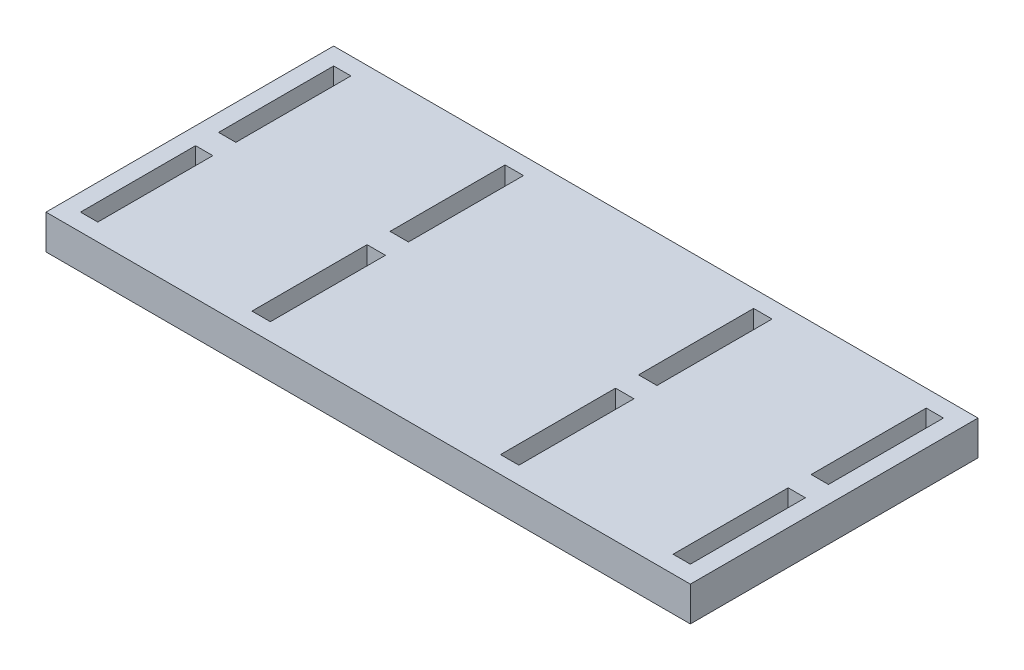
SolidWorks part; units mm, degrees
ref_plane "前视基准面" through (0, 0, 0) normal (0, 0, 1) x (1, 0, 0)
ref_plane "上视基准面" through (0, 0, 0) normal (0, 1, 0) x (1, 0, 0)
ref_plane "右视基准面" through (0, 0, 0) normal (1, 0, 0) x (0, 0, -1)
other "Configuration Table"
sketch "草图1" plane through (0, 0, 0) normal (0, 1, 0) x (1, 0, 0)
  line L0 (56, 0) -> (56, -50)
  line L1 (0, 0) -> (112, 0)
  line L2 (0, 0) -> (0, -50)
  line L3 (0, -50) -> (112, -50)
  line L4 (112, 0) -> (112, -50)
  line L5 (3, -3) -> (6, -3)
  line L6 (3, -3) -> (3, -23)
  line L7 (3, -23) -> (6, -23)
  line L8 (6, -3) -> (6, -23)
  line L9 (0, -25) -> (107.5621, -25)
  line L10 (3, -27) -> (6, -27)
  line L11 (6, -47) -> (6, -27)
  line L12 (3, -47) -> (6, -47)
  line L13 (3, -47) -> (3, -27)
  line L14 (109, -23) -> (106, -23)
  line L15 (106, -3) -> (106, -23)
  line L16 (109, -3) -> (106, -3)
  line L17 (109, -3) -> (109, -23)
  line L18 (109, -47) -> (109, -27)
  line L19 (109, -47) -> (106, -47)
  line L20 (106, -47) -> (106, -27)
  line L21 (109, -27) -> (106, -27)
  line L22 (32.8, -27) -> (36, -27)
  line L23 (32.8, -3) -> (36, -3)
  line L24 (32.8, -3) -> (32.8, -23)
  line L25 (32.8, -23) -> (36, -23)
  line L26 (36, -3) -> (36, -23)
  line L27 (36, -47) -> (36, -27)
  line L28 (32.8, -47) -> (36, -47)
  line L29 (32.8, -47) -> (32.8, -27)
  line L30 (79.2, -47) -> (79.2, -27)
  line L31 (79.2, -47) -> (76, -47)
  line L32 (76, -47) -> (76, -27)
  line L33 (79.2, -27) -> (76, -27)
  line L34 (79.2, -23) -> (76, -23)
  line L35 (76, -3) -> (76, -23)
  line L36 (79.2, -3) -> (76, -3)
  line L37 (79.2, -3) -> (79.2, -23)
  dimension "D1" = 112
  dimension "D2" = 50
  dimension "D3" = 3
  dimension "D4" = 3
  dimension "D5" = 20
  dimension "D6" = 3
  dimension "D7" = 3.2
  dimension "D8" = 20
  dimension "D9" = 20
extrude "凸台-拉伸1" add sketch "草图1" along normal blind 6 contours L2 L9 L0 L1 L5 L8 L7 L6 | L9 L2 L3 L0 L12 L13 L10 L11 | L0 L9 L4 L1 L16 L17 L14 L15 | L9 L0 L3 L4 L21 L18 L19 L20
